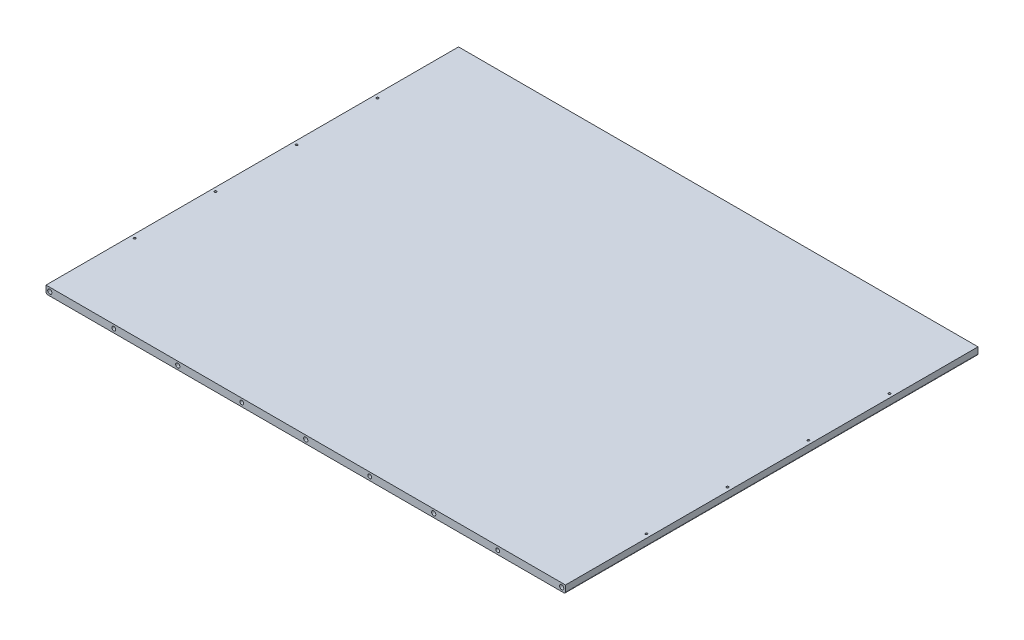
SolidWorks part; units mm, degrees
ref_plane "Front Plane" through (0, 0, 0) normal (0, 0, 1) x (1, 0, 0)
ref_plane "Top Plane" through (0, 0, 0) normal (0, 1, 0) x (1, 0, 0)
ref_plane "Right Plane" through (0, 0, 0) normal (1, 0, 0) x (0, 0, -1)
sketch "Sketch1" plane through (0, 0, 0) normal (0, 1, 0) x (1, 0, 0)
  line L1 (-431.8, -342.9) -> (431.8, -342.9)
  line L2 (-431.8, -342.9) -> (-431.8, 342.9)
  line L3 (-431.8, 342.9) -> (431.8, 342.9)
  line L4 (431.8, -342.9) -> (431.8, 342.9)
  line L5 (-431.8, -342.9) -> (431.8, 342.9) construction
  line L6 (-431.8, 342.9) -> (431.8, -342.9) construction
  point P0 (0, 0)
  dimension "D1" = 685.8
  dimension "D2" = 863.6
extrude "Boss-Extrude1" add sketch "Sketch1" along normal blind 12.7 contours L2 L3 L4 L1
fillet "Fillet1" radius 2.54 2 edges at (-431.8, 0, 0) (431.8, 0, 0)
sketch "Sketch6" plane through (0, 12.7, 0) normal (0, 1, 0) x (1, 0, 0)
  line L4 (0, 342.9) -> (0, -342.9) construction
  line L5 (-431.8, 342.9) -> (431.8, 342.9) construction
  line L6 (-431.8, -342.9) -> (431.8, -342.9) construction
  line L8 (-425.45, -336.55) -> (425.45, -336.55)
  line L9 (425.45, -336.55) -> (425.45, 336.55)
  line L10 (425.45, 336.55) -> (-425.45, 336.55)
  line L11 (-425.45, 336.55) -> (-425.45, -336.55)
  line L12 (-425.45, -336.55) -> (425.45, -336.55) construction
  line L13 (425.45, -336.55) -> (425.45, 336.55) construction
  line L14 (425.45, 336.55) -> (-425.45, 336.55) construction
  line L15 (-425.45, 336.55) -> (-425.45, -336.55) construction
  circle A0 centre (-425.45, 201.93) radius 1.7526
  circle A1 centre (-425.45, 67.31) radius 1.7526
  circle A2 centre (-425.45, -67.31) radius 1.7526
  circle A3 centre (-425.45, -201.93) radius 1.7526
  circle A4 centre (425.45, -201.93) radius 1.7526
  circle A5 centre (425.45, -67.31) radius 1.7526
  circle A6 centre (425.45, 67.31) radius 1.7526
  circle A7 centre (425.45, 201.93) radius 1.7526
  dimension "D3" = 3.5052
  dimension "D2" = 134.62
  dimension "D1" = 6.35
  dimension "D4" = 4
extrude "Cut-Extrude5" cut sketch "Sketch6" against normal through all
sketch "Sketch8" plane through (0, 0, 0) normal (0, -1, 0) x (1, 0, 0)
  line L0 (-425.45, 201.93) -> (-425.45, 342.9) construction
  line L1 (-429.26, 342.9) -> (429.26, 342.9) construction
  circle A0 centre (-425.45, 308.9) radius 6
  circle A1 centre (-212.725, 308.9) radius 6
  circle A2 centre (0, 308.9) radius 6
  circle A3 centre (212.725, 308.9) radius 6
  circle A4 centre (425.45, 308.9) radius 6
  dimension "D2" = 12
  dimension "D3" = 5
  dimension "D1" = 34
extrude "Cut-Extrude7" cut sketch "Sketch8" against normal blind 9.85
sketch "Sketch9" plane through (0, 0, 342.9) normal (0, 0, 1) x (1, 0, 0)
  line L2 (-431.8, 6.35) -> (431.8, 6.35)
  line L3 (-431.8, 6.35) -> (431.8, 6.35) construction
  circle A0 centre (-425.45, 6.35) radius 3.5
  circle A1 centre (-212.725, 6.35) radius 3.5
  circle A2 centre (0, 6.35) radius 3.5
  circle A3 centre (212.725, 6.35) radius 3.5
  circle A4 centre (425.45, 6.35) radius 3.5
  dimension "D3" = 7
  dimension "D2" = 6.35
  dimension "D1" = 6.35
  dimension "D4" = 5
extrude "Cut-Extrude8" cut sketch "Sketch9" against normal blind 34
sketch "Sketch10" plane through (0, 0, 342.9) normal (0, 0, 1) x (1, 0, 0)
  line L0 (-212.725, 6.35) -> (-425.45, 6.35) construction
  circle A0 centre (-319.0875, 6.35) radius 3.175
  circle A1 centre (-106.3625, 6.35) radius 3.175
  circle A2 centre (106.3625, 6.35) radius 3.175
  circle A3 centre (319.0875, 6.35) radius 3.175
  dimension "D1" = 6.35
  dimension "D2" = 4
extrude "Cut-Extrude9" cut sketch "Sketch10" against normal blind 26.67
mirror "Mirror1" about plane through (0, 0, 0) normal (0, 0, 1) of "Cut-Extrude7", "Cut-Extrude9", "Cut-Extrude8"
sketch "Sketch11" plane through (0, 0, 0) normal (0, -1, 0) x (1, 0, 0)
  line L0 (-422.275, -201.93) -> (-422.275, -308.9) construction
  line L3 (-429.26, -313.5351) -> (-429.26, -342.9) construction
  line L4 (-425.45, -201.93) -> (-422.275, -201.93) construction
  line L5 (-425.45, -308.9) -> (-422.275, -308.9) construction
  line L6 (0, 0) -> (-431.8, 0) construction
  line L7 (-431.8, -342.9) -> (-431.8, 342.9) construction
  line L8 (0, 0) -> (0, -342.9) construction
  line L9 (-429.26, -342.9) -> (429.26, -342.9) construction
  circle A0 centre (-422.275, -255.415) radius 1.7526
  circle A1 centre (422.275, -255.415) radius 1.7526
  circle A2 centre (-422.275, 255.415) radius 1.7526
  circle A3 centre (422.275, 255.415) radius 1.7526
  dimension "D2" = 3.5052
  dimension "D1" = 6.985
extrude "Cut-Extrude10" cut sketch "Sketch11" against normal blind 11.43
